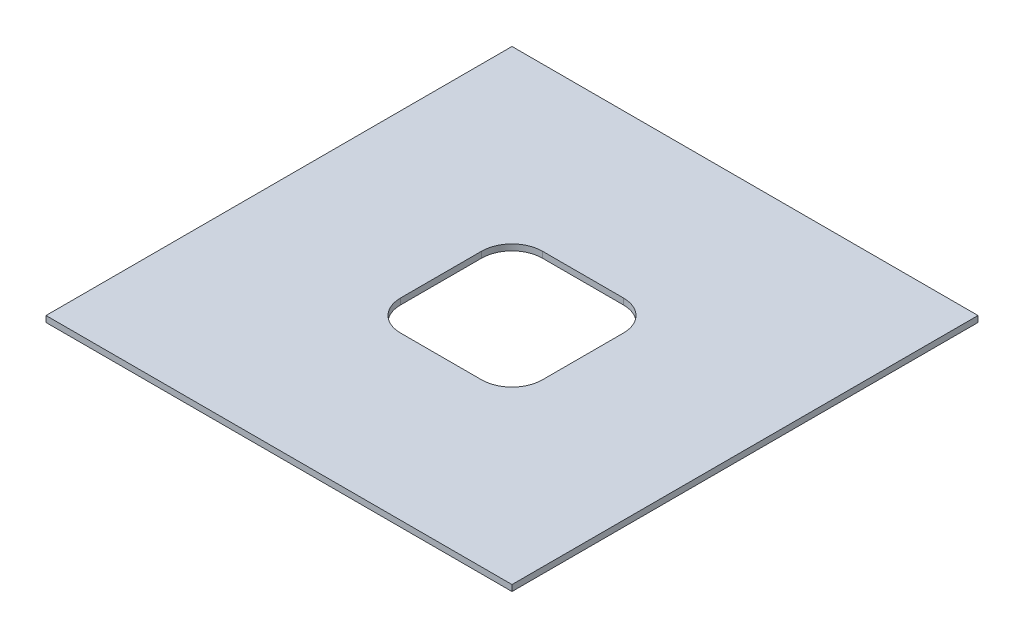
SolidWorks part; units mm, degrees
ref_plane "Front Plane" through (0, 0, 0) normal (0, 0, 1) x (1, 0, 0)
ref_plane "Top Plane" through (0, 0, 0) normal (0, 1, 0) x (1, 0, 0)
ref_plane "Right Plane" through (0, 0, 0) normal (1, 0, 0) x (0, 0, -1)
sketch "Sketch1" plane through (0, 0, 0) normal (0, 1, 0) x (1, 0, 0)
  line L1 (115, 115) -> (-115, 115)
  line L2 (115, 115) -> (115, -115)
  line L3 (115, -115) -> (-115, -115)
  line L4 (-115, 115) -> (-115, -115)
  line L5 (115, 115) -> (-115, -115) construction
  line L6 (115, -115) -> (-115, 115) construction
  line L7 (-20, -35) -> (20, -35)
  line L8 (-35, -20) -> (-35, 20)
  line L9 (-20, 35) -> (20, 35)
  line L10 (35, -20) -> (35, 20)
  line L11 (-35, -35) -> (35, 35) construction
  line L12 (-35, 35) -> (35, -35) construction
  arc A0 (-20, 35) -> (-35, 20) centre (-20, 20) ccw
  arc A1 (-20, -35) -> (-35, -20) centre (-20, -20) cw
  arc A2 (35, -20) -> (20, -35) centre (20, -20) cw
  arc A3 (20, 35) -> (35, 20) centre (20, 20) cw
  point P0 (0, 0)
  point P6 (0, 0)
  dimension "D5" = 15
  dimension "D6" = 15
  dimension "D7" = 15
  dimension "D8" = 15
  dimension "D1" = 230
  dimension "D2" = 230
  dimension "D3" = 70
  dimension "D4" = 70
extrude "Boss-Extrude1" add sketch "Sketch1" along normal blind 3
